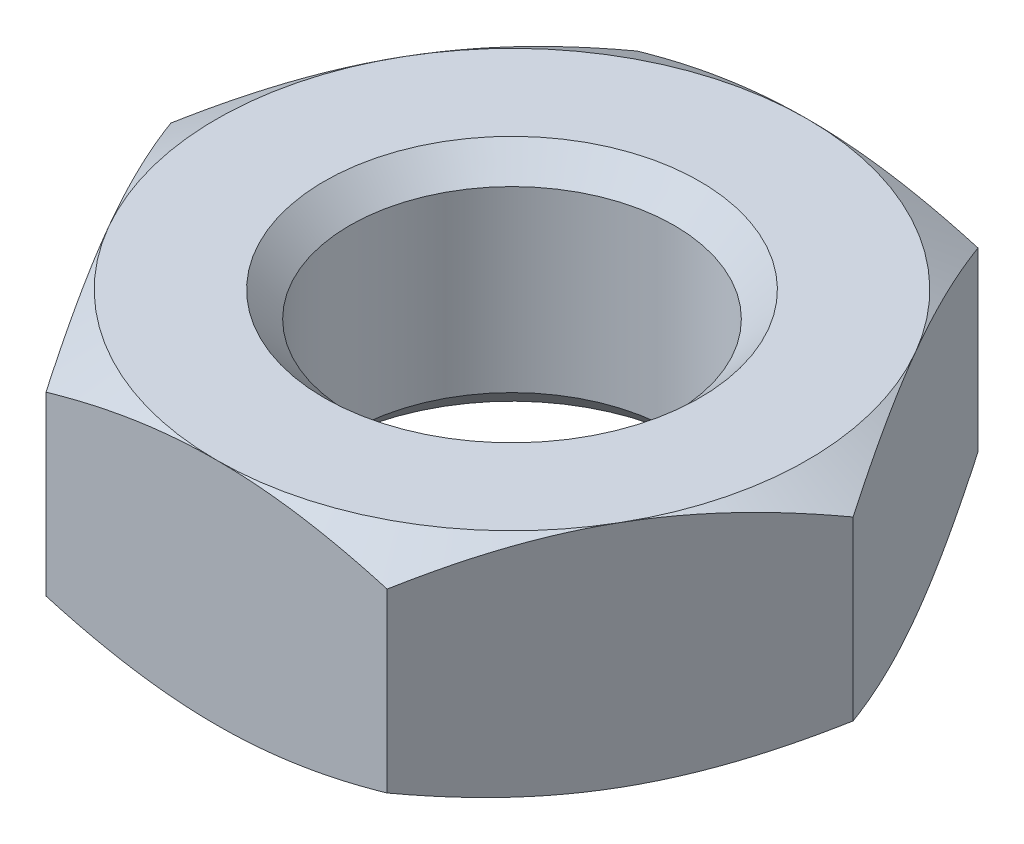
SolidWorks part; units mm, degrees
ref_plane "Front Plane" through (0, 0, 0) normal (0, 0, 1) x (1, 0, 0)
ref_plane "Top Plane" through (0, 0, 0) normal (0, 1, 0) x (1, 0, 0)
ref_plane "Right Plane" through (0, 0, 0) normal (1, 0, 0) x (0, 0, -1)
sketch "Sketch1" plane through (0, 0, 0) normal (0, 1, 0) x (1, 0, 0)
  line L1 (3.6806, -6.375) -> (7.3612, 0)
  line L2 (7.3612, 0) -> (3.6806, 6.375)
  line L3 (3.6806, 6.375) -> (-3.6806, 6.375)
  line L4 (-3.6806, 6.375) -> (-7.3612, 0)
  line L5 (-7.3612, 0) -> (-3.6806, -6.375)
  line L6 (-3.6806, -6.375) -> (3.6806, -6.375)
  circle A0 centre (0, 0) radius 6.375 construction
  dimension "D1" = 12.75
extrude "Boss-Extrude1" add sketch "Sketch1" along normal mid plane 4.95
sketch "Sketch2" plane through (0, 2.475, 0) normal (0, 1, 0) x (1, 0, 0)
  line L0 (-3.6806, -6.375) -> (3.6806, -6.375) construction
  circle A0 centre (0, 0) radius 6.375
extrude "Cut-Extrude1" cut sketch "Sketch2" against normal blind 4.95 draft 60 flip side to cut
mirror "Mirror1" about plane through (0, 0, 0) normal (0, 1, 0) of "Cut-Extrude1"
hole_wizard "M8x1.0 Tapped Hole1" positions "Sketch3" profile "Sketch5" tap size "M8x1.0" standard "ANSI Metric" end condition through all
sketch "Sketch3" plane through (0, 2.475, 0) normal (0, 1, 0) x (1, 0, 0)
  point P0 (0, 0)
sketch "Sketch5" plane through (0, 2.475, 0) normal (1, 0, 0) x (0, 0, 1)
  line L0 (0, 0) -> (0, 4.95)
  line L1 (0, 4.95) -> (4.05, 4.95)
  line L2 (3.5, 4.4) -> (3.5, 0.55)
  line L3 (3.5, 0.55) -> (4.05, 0)
  line L5 (4.05, 0) -> (0, 0)
  line L6 (-3.5, 0.55) -> (-4.05, 0) construction
  line L7 (4.05, 4.95) -> (3.5, 4.4)
  line L8 (-4.05, 4.95) -> (-3.5, 4.4) construction
  line L11 (0, -6.35) -> (0, 107.95) construction
  dimension "Thru Tap Drill Dia." = 7
  dimension "Thru Tap Drill Depth" = 4.95
  dimension "Near C'Sink Dia." = 8.1
  dimension "Near C'Sink Angle" = 90
  dimension "Far C'Sink Dia." = 8.1
  dimension "Far C'Sink Angle" = 90
cosmetic thread "Hole Thread1" parameters "D2"=8
move or copy body "Body-Move/Copy1" [suppressed] bodies to move or copy 104
